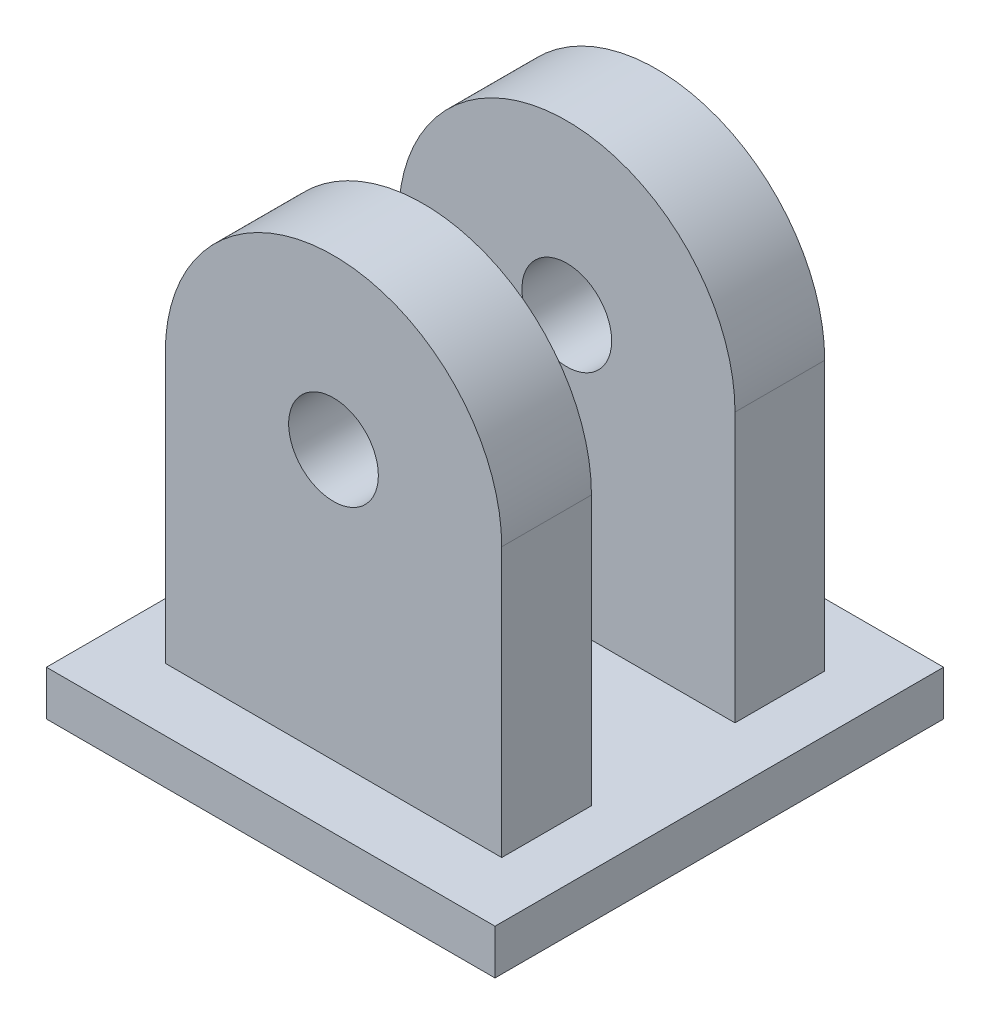
SolidWorks part; units mm, degrees
ref_plane "Front" through (0, 0, 0) normal (0, 0, 1) x (1, 0, 0)
ref_plane "Top" through (0, 0, 0) normal (0, 1, 0) x (1, 0, 0)
ref_plane "Right" through (0, 0, 0) normal (1, 0, 0) x (0, 0, -1)
sketch "Croquis1" plane through (0, 0, 0) normal (0, 0, 1) x (1, 0, 0)
  line L0 (-3.75, 0) -> (-3.75, -6)
  line L1 (3.75, 0) -> (3.75, -6)
  line L2 (3.75, -6) -> (-3.75, -6)
  arc A0 (3.75, 0) -> (-3.75, 0) centre (0, 0) ccw
  circle A1 centre (0, 0) radius 1
  dimension "D1" = 2
  dimension "D2" = 7.5
  dimension "D3" = 6
extrude "Saliente-Extruir1" add sketch "Croquis1" along normal blind 2
pattern_linear "MatrizL1" count 2 spacing 5.2 along (0, 0, 1) of "Saliente-Extruir1"
sketch "Croquis2" plane through (0, -6, 0) normal (0, -1, 0) x (1, 0, 0)
  line L0 (0, 0) -> (0, 7.2) construction
  line L5 (-3.75, 0) -> (3.75, 0) construction
  line L6 (-3.75, 7.2) -> (3.75, 7.2) construction
  line L8 (5, 8.6) -> (-5, 8.6)
  line L9 (5, 8.6) -> (5, -1.4)
  line L10 (5, -1.4) -> (-5, -1.4)
  line L11 (-5, 8.6) -> (-5, -1.4)
  line L12 (5, 8.6) -> (-5, -1.4) construction
  line L13 (5, -1.4) -> (-5, 8.6) construction
  point P8 (0, 3.6)
  dimension "D1" = 10
extrude "Saliente-Extruir2" add sketch "Croquis2" along normal blind 1
sketch "Croquis4" plane through (0, -7, 0) normal (0, -1, 0) x (1, 0, 0)
  line L0 (0, 8.6) -> (0, -1.4) construction
  line L1 (5, 8.6) -> (-5, 8.6) construction
  line L2 (-5, -1.4) -> (5, -1.4) construction
  circle A0 centre (0, 3.6) radius 4.55
  circle A1 centre (0, 3.6) radius 4
  dimension "D1" = 9.1
  dimension "D2" = 8
